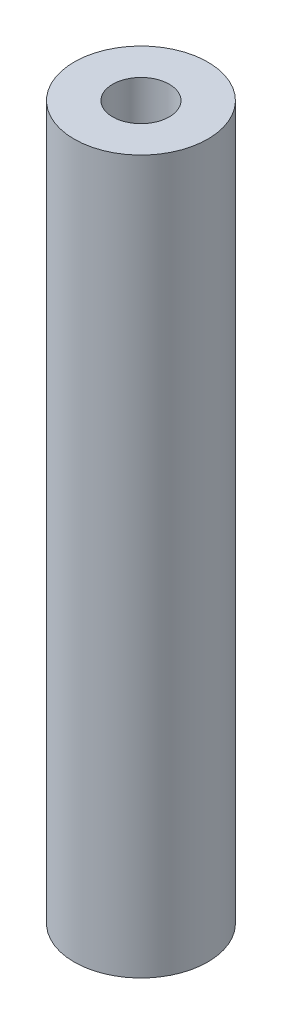
SolidWorks part; units mm, degrees
ref_plane "Front Plane" through (0, 0, 0) normal (0, 0, 1) x (1, 0, 0)
ref_plane "Top Plane" through (0, 0, 0) normal (0, 1, 0) x (1, 0, 0)
ref_plane "Right Plane" through (0, 0, 0) normal (1, 0, 0) x (0, 0, -1)
sketch "Sketch1" plane through (0, 0, 0) normal (0, 1, 0) x (1, 0, 0)
  circle A0 centre (0, 0) radius 2.0193
  circle A1 centre (0, 0) radius 4.7625
  dimension "D1" = 9.525
  dimension "D2" = 4.0386
extrude "Boss-Extrude1" add sketch "Sketch1" along normal blind 50.8
